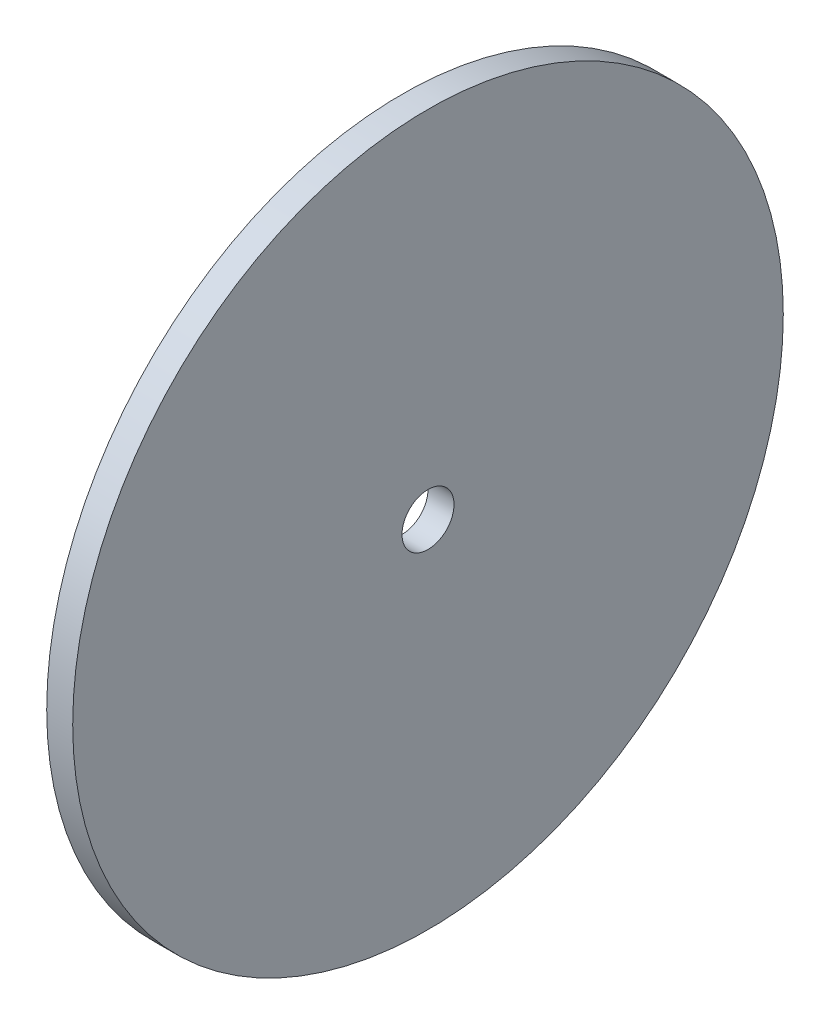
SolidWorks part; units mm, degrees
ref_plane "Front Plane" through (0, 0, 0) normal (0, 0, 1) x (1, 0, 0)
ref_plane "Top Plane" through (0, 0, 0) normal (0, 1, 0) x (1, 0, 0)
ref_plane "Right Plane" through (0, 0, 0) normal (1, 0, 0) x (0, 0, -1)
sketch "Sketch1" plane through (0, 0, 0) normal (1, 0, 0) x (0, 0, -1)
  circle A0 centre (0, 0) radius 20.5
  circle A1 centre (0, 0) radius 1.5
  dimension "D1" = 41
  dimension "D2" = 3
extrude "Boss-Extrude1" add sketch "Sketch1" along normal blind 1.5
